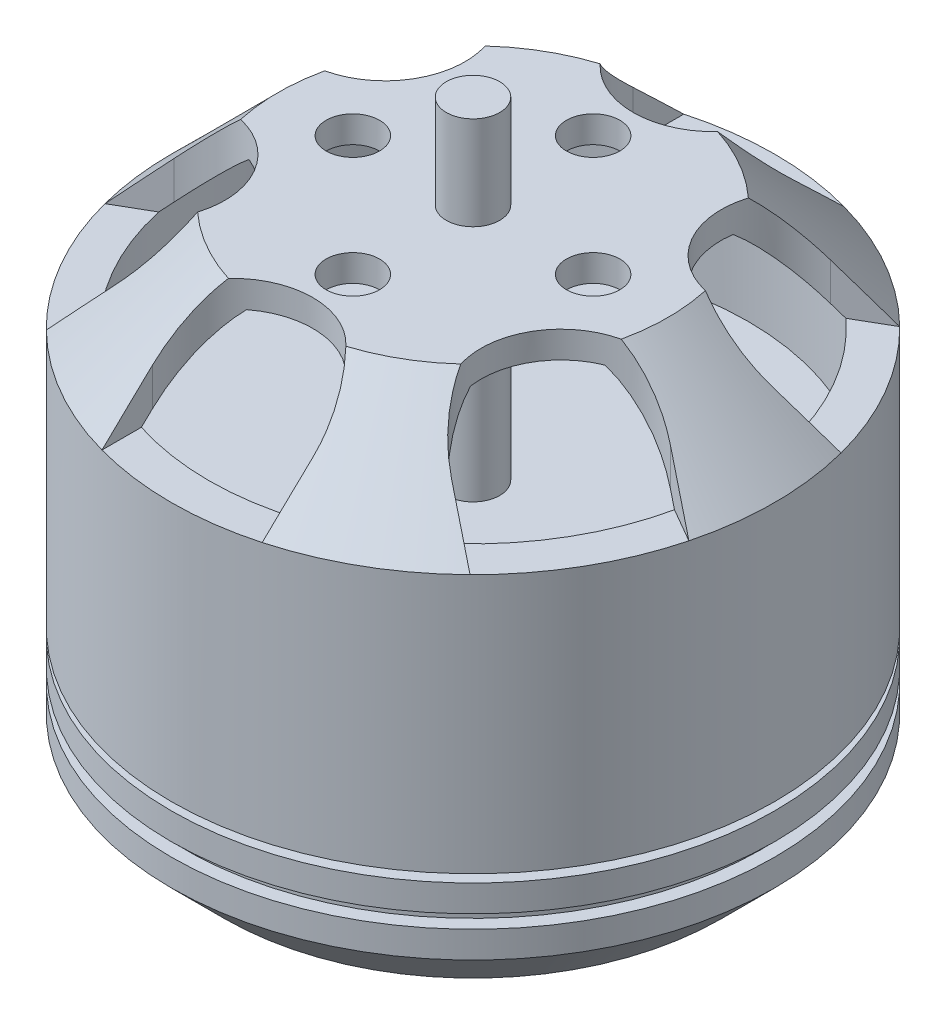
SolidWorks part; units mm, degrees
material "1023 Carbon Steel Sheet (SS)"
ref_plane "Front Plane" through (0, 0, 0) normal (0, 0, 1) x (1, 0, 0)
ref_plane "Top Plane" through (0, 0, 0) normal (0, 1, 0) x (1, 0, 0)
ref_plane "Right Plane" through (0, 0, 0) normal (1, 0, 0) x (0, 0, -1)
sketch "Sketch1" plane through (0, 0, 0) normal (0, 0, 1) x (1, 0, 0)
  line L0 (0, 22) -> (0, -1.8)
  line L1 (0, -1.8) -> (1, -1.8)
  line L2 (1, -1.8) -> (1, 0)
  line L3 (1, 0) -> (9.3, 0)
  line L4 (9.3, 0) -> (11.3, 2)
  line L5 (11.3, 2) -> (11.3, 3)
  line L6 (11.3, 14.5) -> (7.3, 18.5)
  line L7 (7.3, 18.5) -> (1, 18.5)
  line L8 (1, 18.5) -> (1, 22)
  line L9 (1, 22) -> (0, 22)
  line L10 (2, 17.5) -> (6.8858, 17.5)
  line L11 (6.8858, 17.5) -> (10.3, 14.0858)
  line L12 (10.3, 14.0858) -> (10.3, 9.5764)
  line L13 (10.3, 9.5764) -> (1, 9.5764)
  line L14 (1, 9.5764) -> (1, 16.5)
  line L15 (1, 16.5) -> (2, 16.5)
  line L16 (2, 16.5) -> (2, 17.5)
  line L17 (11.3, 3) -> (10.8, 3)
  line L18 (10.8, 3) -> (10.8, 3.5)
  line L19 (10.8, 3.5) -> (11.3, 3.5)
  line L20 (11.3, 4.5) -> (9.3, 4.5)
  line L21 (9.3, 4.5) -> (9.3, 4.8)
  line L22 (9.3, 4.8) -> (11.3, 4.8)
  line L23 (11.3, 4.8) -> (11.3, 14.5)
  line L24 (11.3, 3.5) -> (11.3, 4.5)
  point P25 (11.05, 3.5)
  dimension "D1" = 23.8
  dimension "D2" = 1.8
  dimension "D3" = 2
  dimension "D4" = 11.3
  dimension "45" = 45
  dimension "D5" = 1
  dimension "D6" = 1
  dimension "D7" = 3.5
  dimension "D8" = 45
  dimension "D9" = 1
  dimension "D10" = 1
  dimension "D11" = 1
  dimension "D12" = 1
  dimension "D13" = 1
  dimension "D14" = 1
  dimension "D15" = 4
  dimension "D16" = 0.5
  dimension "D17" = 0.5
  dimension "D18" = 2
  dimension "D19" = 0.3
  dimension "D20" = 1
  dimension "D21" = 1
revolve "Revolve1" add sketch "Sketch1" angle 360 about L0
sketch "Sketch2" plane through (0, 18.5, 0) normal (0, 1, 0) x (1, 0, 0)
  line L0 (0, 0) -> (0, 9) construction
  line L1 (-3, 9) -> (-3, 15.8146)
  line L2 (-3, 15.8146) -> (3, 15.8146)
  line L3 (3, 15.8146) -> (3, 9)
  line L4 (6.2942, 7.0981) -> (12.1958, 10.5054)
  line L5 (15.1958, 5.3092) -> (9.2942, 1.9019)
  line L6 (12.1958, 10.5054) -> (15.1958, 5.3092)
  line L7 (9.2942, -1.9019) -> (15.1958, -5.3092)
  line L8 (12.1958, -10.5054) -> (6.2942, -7.0981)
  line L9 (15.1958, -5.3092) -> (12.1958, -10.5054)
  line L10 (3, -9) -> (3, -15.8146)
  line L11 (-3, -15.8146) -> (-3, -9)
  line L12 (3, -15.8146) -> (-3, -15.8146)
  line L13 (-6.2942, -7.0981) -> (-12.1958, -10.5054)
  line L14 (-15.1958, -5.3092) -> (-9.2942, -1.9019)
  line L15 (-12.1958, -10.5054) -> (-15.1958, -5.3092)
  line L16 (-9.2942, 1.9019) -> (-15.1958, 5.3092)
  line L17 (-12.1958, 10.5054) -> (-6.2942, 7.0981)
  line L18 (-15.1958, 5.3092) -> (-12.1958, 10.5054)
  circle A0 centre (0, 0) radius 4.5 construction
  circle A1 centre (0, 4.5) radius 1
  circle A2 centre (4.5, 0) radius 1
  circle A3 centre (0, -4.5) radius 1
  circle A4 centre (-4.5, 0) radius 1
  arc A5 (-3, 9) -> (3, 9) centre (0, 9) ccw
  arc A6 (6.2942, 7.0981) -> (9.2942, 1.9019) centre (7.7942, 4.5) ccw
  arc A7 (9.2942, -1.9019) -> (6.2942, -7.0981) centre (7.7942, -4.5) ccw
  arc A8 (3, -9) -> (-3, -9) centre (0, -9) ccw
  arc A9 (-6.2942, -7.0981) -> (-9.2942, -1.9019) centre (-7.7942, -4.5) ccw
  arc A10 (-9.2942, 1.9019) -> (-6.2942, 7.0981) centre (-7.7942, 4.5) ccw
  point P14 (0, 0)
  point P44 (0, 0)
  dimension "D1" = 9
  dimension "D2" = 2
  dimension "D5" = 6
  dimension "D4" = 9
  dimension "D3" = 4
  dimension "D6" = 6
extrude "Cut-Extrude1" cut sketch "Sketch2" against normal blind 4
sketch "Sketch3" plane through (0, 0, 0) normal (0, -1, 0) x (1, 0, 0)
  circle A0 centre (0, 0) radius 8 construction
  circle A1 centre (0, 0) radius 6 construction
  circle A2 centre (0, 6) radius 1
  circle A3 centre (0, -6) radius 1
  circle A4 centre (8, 0) radius 1
  circle A5 centre (-8, 0) radius 1
  dimension "D1" = 16
  dimension "D2" = 12
  dimension "D3" = 2
extrude "Cut-Extrude2" cut sketch "Sketch3" against normal blind 3
